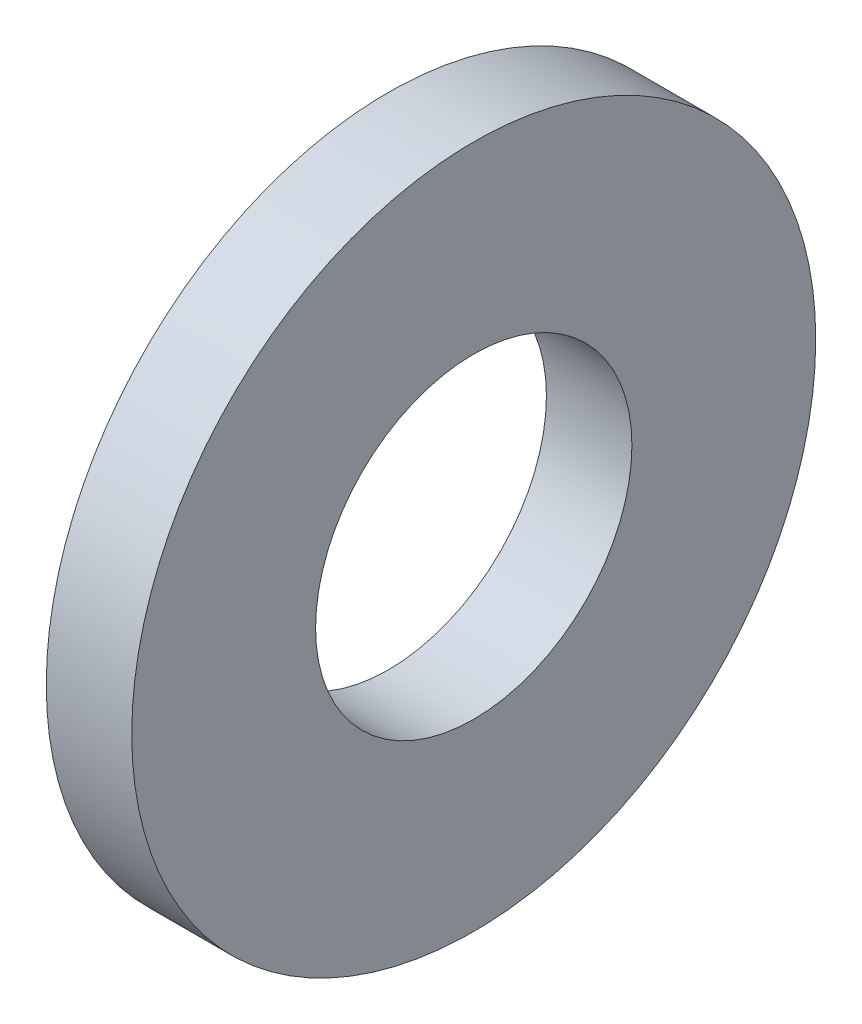
SolidWorks part; units mm, degrees
ref_plane "Plane1" through (0, 0, 0) normal (0, 0, 1) x (1, 0, 0)
ref_plane "Plane2" through (0, 0, 0) normal (0, 1, 0) x (1, 0, 0)
ref_plane "Plane3" through (0, 0, 0) normal (1, 0, 0) x (0, 0, -1)
sketch "Sketch1" plane through (0, 0, 0) normal (1, 0, 0) x (0, 0, -1)
  circle A0 centre (0, 0) radius 3.7
  circle A1 centre (0, 0) radius 8
  dimension "Insid_dia" = 7.4
  dimension "OutsideDia" = 16
extrude "Base-Extrude" add sketch "Sketch1" along normal blind 2
